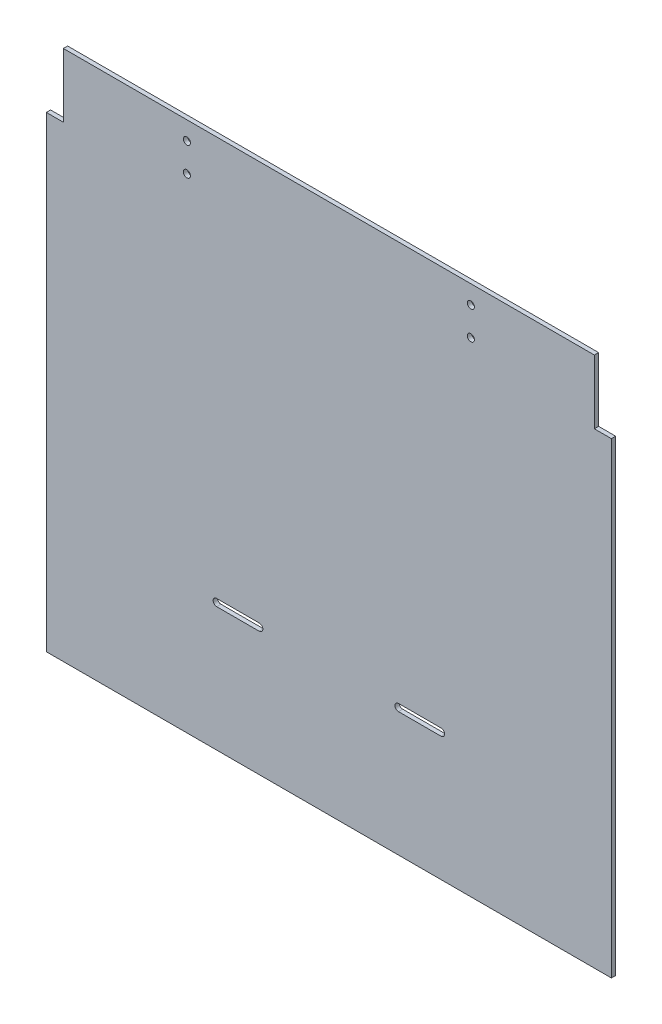
SolidWorks part; units mm, degrees
material "Acrylic (Medium-high impact)"
ref_plane "Front Plane" through (0, 0, 0) normal (0, 0, 1) x (1, 0, 0)
ref_plane "Top Plane" through (0, 0, 0) normal (0, 1, 0) x (1, 0, 0)
ref_plane "Right Plane" through (0, 0, 0) normal (1, 0, 0) x (0, 0, -1)
sketch "Sketch1" plane through (0, 0, 0) normal (0, 0, 1) x (1, 0, 0)
  line L1 (-199, -187) -> (199, -187)
  line L2 (-199, -187) -> (-199, 187)
  line L3 (-199, 187) -> (199, 187)
  line L4 (199, -187) -> (199, 187)
  line L5 (-199, -187) -> (199, 187) construction
  line L6 (-199, 187) -> (199, -187) construction
  point P0 (0, 0)
  dimension "D1" = 398
  dimension "D2" = 374
extrude "Boss-Extrude1" add sketch "Sketch1" along normal blind 3
sketch "Sketch2" plane through (0, 0, 0) normal (0, 0, -1) x (-1, 0, 0)
  line L0 (-199, -187) -> (-199, 187) construction
  line L1 (-199, 187) -> (-187, 187)
  line L2 (-199, 187) -> (-199, 142)
  line L3 (-199, 142) -> (-187, 142)
  line L4 (-1000, 0) -> (49000, 0) construction
  line L5 (-187, 187) -> (-187, 142)
  line L6 (0, -1000) -> (0, 49000) construction
  line L8 (-199, 187) -> (199, 187) construction
  line L10 (-932.2042, 164.06) -> (49067.7958, 164.06) construction
  line L11 (187, 187) -> (187, 142)
  line L12 (199, 142) -> (187, 142)
  line L13 (199, 187) -> (199, 142)
  line L14 (199, 187) -> (187, 187)
  circle A6 centre (-100, 174.06) radius 2.5
  circle A8 centre (-100, 154.06) radius 2.5
  circle A9 centre (100, 154.06) radius 2.5
  circle A10 centre (100, 174.06) radius 2.5
  dimension "D2" = 22.94
  dimension "D3" = 100
  dimension "D5" = 10
  dimension "D6" = 5
  dimension "D1" = 12
  dimension "D4" = 45
extrude "Cut-Extrude1" cut sketch "Sketch2" against normal up to next
sketch "Sketch3" plane through (0, 0, 0) normal (0, 0, -1) x (-1, 0, 0)
  line L0 (0, -1000) -> (0, 49000) construction
  line L1 (-1073.3062, -97) -> (48926.6938, -97) construction
  line L2 (199, -187) -> (-199, -187) construction
  circle A0 centre (64, -97) radius 2.5
  circle A1 centre (-64, -97) radius 2.5
  dimension "D2" = 64
  dimension "D3" = 5
  dimension "D1" = 90
extrude "Cut-Extrude2" cut sketch "Sketch3" against normal up to next
sketch "Sketch4" plane through (0, 0, 0) normal (0, 0, -1) x (-1, 0, 0)
  line L0 (0, -1187) -> (0, 48813) construction
  line L1 (199, -187) -> (-199, -187) construction
  line L2 (-936, -97) -> (49064, -97) construction
  line L3 (49, -97) -> (79, -97) construction
  line L4 (49, -94.5) -> (79, -94.5)
  line L5 (49, -99.5) -> (79, -99.5)
  line L6 (-49, -97) -> (-79, -97) construction
  line L7 (-49, -94.5) -> (-79, -94.5)
  line L8 (-49, -99.5) -> (-79, -99.5)
  arc A0 (49, -94.5) -> (49, -99.5) centre (49, -97) ccw
  arc A1 (79, -99.5) -> (79, -94.5) centre (79, -97) ccw
  circle A2 centre (64, -97) radius 2.5 construction
  arc A3 (-49, -94.5) -> (-49, -99.5) centre (-49, -97) cw
  arc A4 (-79, -99.5) -> (-79, -94.5) centre (-79, -97) cw
  point P5 (0, -187)
  point P10 (64, -97)
  point P19 (-64, -97)
  dimension "D1" = 30
extrude "Cut-Extrude3" cut sketch "Sketch4" against normal through all
